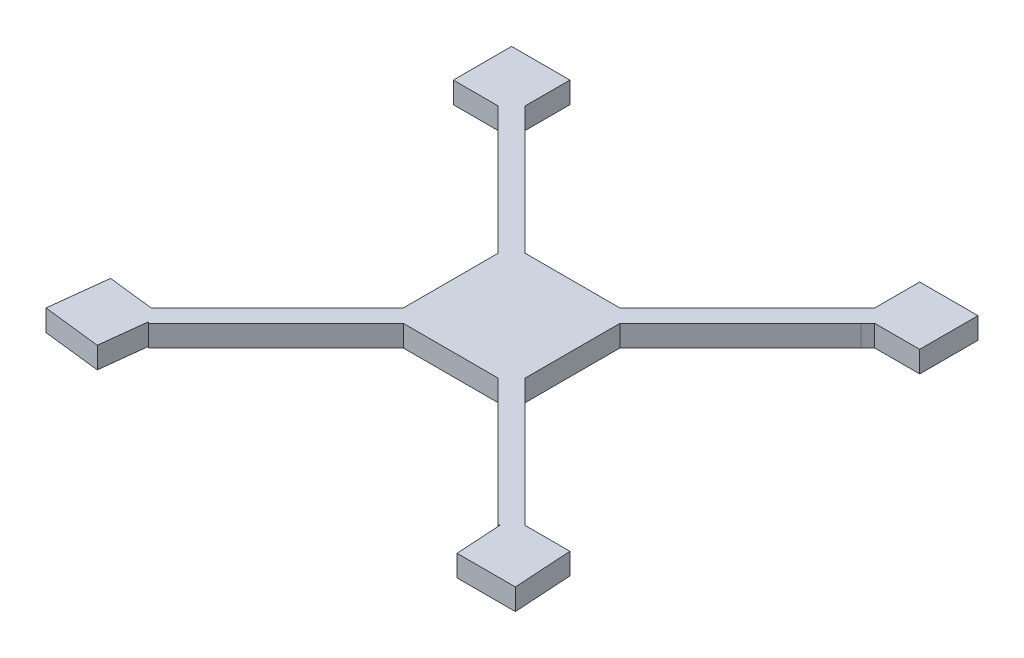
SolidWorks part; units mm, degrees
material "PVC 0.007 Plasticized"
ref_plane "Front Plane" through (0, 0, 0) normal (0, 0, 1) x (1, 0, 0)
ref_plane "Top Plane" through (0, 0, 0) normal (0, 1, 0) x (1, 0, 0)
ref_plane "Right Plane" through (0, 0, 0) normal (1, 0, 0) x (0, 0, -1)
sketch "Sketch1" plane through (0, 0, 0) normal (0, 1, 0) x (1, 0, 0)
  line L0 (0, 0) -> (-71.842, 71.842)
  line L1 (0, 0) -> (0, -56.4444)
  line L2 (0, -56.4444) -> (-71.842, -128.2865)
  line L3 (-71.842, -128.2865) -> (-63.8805, -136.2481)
  line L4 (-63.8805, -136.2481) -> (7.9616, -64.406)
  line L5 (7.9616, -64.406) -> (64.406, -64.406)
  line L6 (64.406, -64.406) -> (136.2481, -136.2481)
  line L7 (136.2481, -136.2481) -> (144.2097, -128.2865)
  line L8 (144.2097, -128.2865) -> (72.3676, -56.4444)
  line L9 (72.3676, -56.4444) -> (72.3676, 0)
  line L10 (72.3676, 0) -> (144.2097, 71.842)
  line L11 (144.2097, 71.842) -> (136.2481, 79.8036)
  line L12 (136.2481, 79.8036) -> (64.406, 7.9616)
  line L13 (64.406, 7.9616) -> (7.9616, 7.9616)
  line L14 (7.9616, 7.9616) -> (-63.8805, 79.8036)
  line L15 (-63.8805, 79.8036) -> (-71.842, 71.842)
  dimension "D1" = 101.6
  dimension "D2" = 101.6
extrude "Boss-Extrude1" add sketch "Sketch1" along normal blind 12.7
sketch "Sketch4" plane through (0, 12.7, 0) normal (0, 1, 0) x (1, 0, 0)
  line L0 (-63.8805, 79.8036) -> (-71.842, 71.842) construction
  line L1 (-102.5494, 110.511) -> (-67.8613, 110.511)
  line L2 (-102.5494, 110.511) -> (-102.5494, 75.8228)
  line L3 (-102.5494, 75.8228) -> (-67.8613, 75.8228)
  line L4 (-67.8613, 110.511) -> (-67.8613, 75.8228)
  line L5 (-102.5494, 110.511) -> (-67.8613, 75.8228) construction
  line L6 (-102.5494, 75.8228) -> (-67.8613, 110.511) construction
  line L7 (-71.842, 71.842) -> (-75.8228, 75.8228)
  line L8 (-75.8228, 75.8228) -> (-67.8613, 75.8228)
  line L9 (-71.842, 71.842) -> (-75.8228, 75.8228)
  line L10 (-75.8228, 75.8228) -> (-67.8613, 75.8228)
  line L11 (-71.842, 71.842) -> (-75.8228, 75.8228)
  line L12 (-71.842, 71.842) -> (-75.8228, 75.8228)
  line L13 (-71.842, 71.842) -> (-63.9236, 79.7605)
  line L14 (-75.8228, 75.8228) -> (-67.9044, 83.7413)
  line L15 (-63.9236, 79.7605) -> (-67.9044, 83.7413)
  line L16 (140.2289, 75.8228) -> (140.2289, 110.511)
  line L17 (144.2097, 71.842) -> (136.2481, 79.8036) construction
  line L18 (140.2289, 110.511) -> (174.9171, 110.511)
  line L19 (174.9171, 110.511) -> (174.9171, 75.8228)
  line L20 (174.9171, 75.8228) -> (140.2289, 75.8228)
  line L21 (136.2481, 79.8036) -> (140.2289, 83.7413)
  line L22 (136.2481, 79.8036) -> (144.1685, 71.7965)
  line L23 (140.2289, 83.7413) -> (148.1493, 75.7342)
  line L24 (144.1685, 71.7965) -> (148.1493, 75.7342)
  line L25 (140.2289, -132.2673) -> (174.9171, -132.2673)
  line L26 (136.2481, -136.2481) -> (144.2097, -128.2865) construction
  line L27 (140.2289, -132.2673) -> (142.3969, -166.8876)
  line L28 (174.9171, -132.2673) -> (177.0851, -166.8876)
  line L29 (177.0851, -166.8876) -> (142.3969, -166.8876)
  line L30 (136.2481, -136.2481) -> (144.2097, -128.2865)
  line L31 (136.2481, -136.2481) -> (140.0772, -140.0772)
  line L32 (144.2097, -128.2865) -> (148.0387, -132.1156)
  line L33 (140.0772, -140.0772) -> (148.0387, -132.1156)
  line L34 (-67.8613, -132.2673) -> (-71.8237, -166.7284)
  line L35 (-71.842, -128.2865) -> (-63.8805, -136.2481) construction
  line L36 (-67.8613, -132.2673) -> (-102.3224, -128.3048)
  line L37 (-102.3224, -128.3048) -> (-106.2849, -162.7659)
  line L38 (-106.2849, -162.7659) -> (-71.8237, -166.7284)
  line L39 (-71.842, -128.2865) -> (-63.8805, -136.2481)
  line L40 (-71.842, -128.2865) -> (-75.8475, -132.2919)
  line L41 (-63.8805, -136.2481) -> (-67.8859, -140.2535)
  line L42 (-75.8475, -132.2919) -> (-67.8859, -140.2535)
  point P0 (-85.2053, 93.1669)
  line M14 (72.3676, 0) -> (144.2097, 71.842)
  line M15 (144.2097, 71.842) -> (136.2481, 79.8036)
  line M19 (-63.8805, 79.8036) -> (-71.842, 71.842)
extrude "Boss-Extrude6" add sketch "Sketch4" against normal blind 12.7 contours L15 L4 M19 | L4 L15 L14 L3 | L7 L3 M19 | L42 L40 L36 L37 L38 L34 | L33 L27 L29 L28 L25 | L16 L23 L20 L19 L18 | L21 L16 M15 | L23 L16 L20 | L22 L24 L23 L20 M15 M14
sketch "Sketch10" plane through (0, 0, 0) normal (0, -1, 0) x (-1, 0, 0)
  line L0 (102.3224, -128.3048) -> (71.8237, -166.7284)
  line L1 (97.0596, -146.9987) -> (88.8353, -157.3601)
  line L2 (85.3108, -137.6731) -> (77.0865, -148.0345)
  line L3 (-211.6594, -28.2222) -> (142.3311, -28.2222)
  line L4 (85.3108, 81.2287) -> (77.0865, 91.5901)
  line L5 (97.0596, 90.5542) -> (88.8353, 100.9157)
  line L6 (-36.1838, -172.6603) -> (-36.1838, 107.6974)
  line L7 (-169.4273, -146.9987) -> (-161.2029, -157.3601)
  line L8 (-157.6785, -137.6731) -> (-149.4541, -148.0345)
  line L9 (-169.4273, 90.5542) -> (-161.2029, 100.9157)
  line L10 (-157.6785, 81.2287) -> (-149.4541, 91.5901)
  arc A0 (97.0596, -146.9987) -> (85.3108, -137.6731) centre (87.0731, -147.5166) ccw
  arc A1 (77.0865, -148.0345) -> (88.8353, -157.3601) centre (87.0731, -147.5166) ccw
  arc A2 (97.0596, 90.5542) -> (85.3108, 81.2287) centre (87.0731, 91.0722) cw
  arc A3 (77.0865, 91.5901) -> (88.8353, 100.9157) centre (87.0731, 91.0722) cw
  arc A4 (-169.4273, -146.9987) -> (-157.6785, -137.6731) centre (-159.4407, -147.5166) cw
  arc A5 (-149.4541, -148.0345) -> (-161.2029, -157.3601) centre (-159.4407, -147.5166) cw
  arc A6 (-149.4541, 91.5901) -> (-161.2029, 100.9157) centre (-159.4407, 91.0722) ccw
  arc A7 (-169.4273, 90.5542) -> (-157.6785, 81.2287) centre (-159.4407, 91.0722) ccw
  dimension "D1" = 15
  dimension "D3" = 20
  dimension "D2" = 7.5
extrude "Cut-Extrude1" cut sketch "Sketch10" against normal blind 10 contours A3 L4 A2 L5 | L9 A7 L10 A6 | A5 L8 A4 L7 | A1 L1 A0 L2
